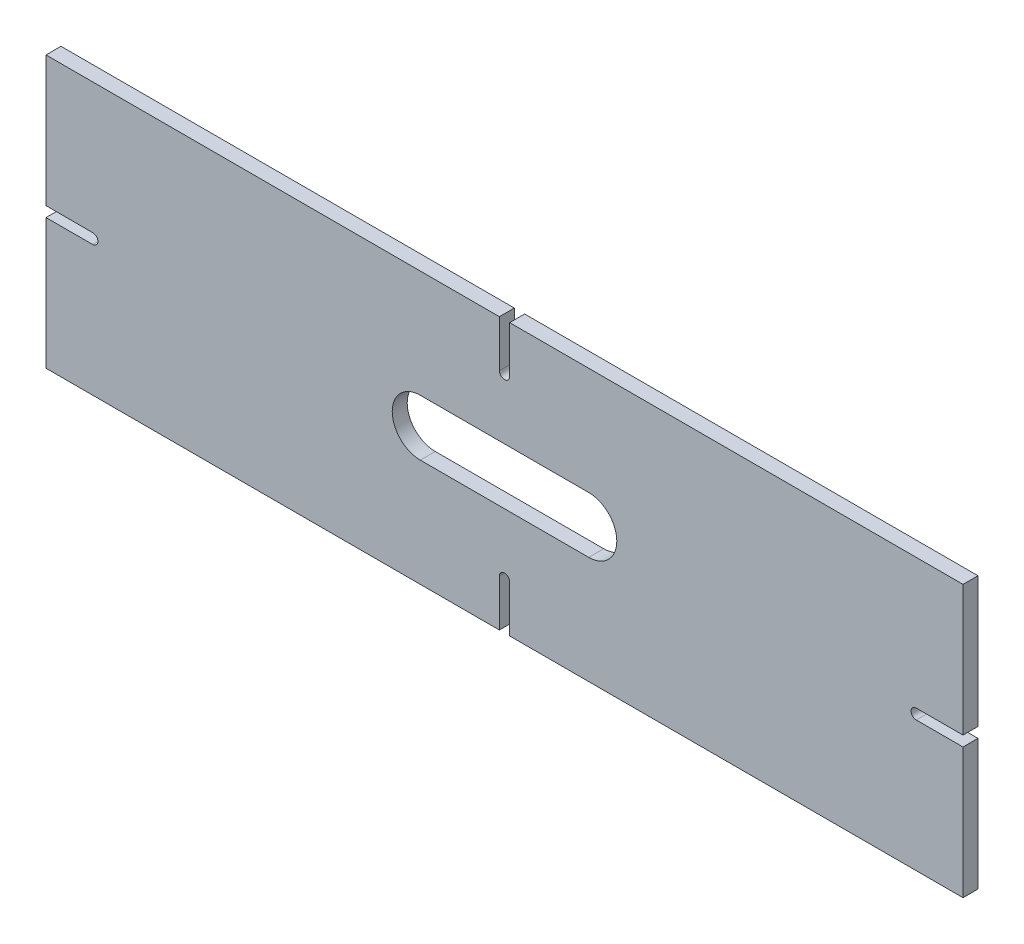
SolidWorks part; units mm, degrees
ref_plane "Front Plane" through (0, 0, 0) normal (0, 0, 1) x (1, 0, 0)
ref_plane "Top Plane" through (0, 0, 0) normal (0, 1, 0) x (1, 0, 0)
ref_plane "Right Plane" through (0, 0, 0) normal (1, 0, 0) x (0, 0, -1)
sketch "Sketch1" plane through (0, 0, 0) normal (0, 0, 1) x (1, 0, 0)
  line L0 (0, 72.5) -> (0, 47.5) construction
  line L1 (-245, -72.5) -> (245, -72.5)
  line L2 (-245, -72.5) -> (-245, 72.5)
  line L3 (-245, 72.5) -> (245, 72.5)
  line L4 (245, -72.5) -> (245, 72.5)
  line L5 (-245, -72.5) -> (245, 72.5) construction
  line L6 (-245, 72.5) -> (245, -72.5) construction
  line L7 (2.75, 72.5) -> (2.75, 47.5)
  line L8 (-2.75, 72.5) -> (-2.75, 47.5)
  line L9 (245, 0) -> (220, 0) construction
  line L10 (245, -2.75) -> (220, -2.75)
  line L11 (245, 2.75) -> (220, 2.75)
  line L12 (0, -72.5) -> (0, -47.5) construction
  line L13 (-2.75, -72.5) -> (-2.75, -47.5)
  line L14 (2.75, -72.5) -> (2.75, -47.5)
  line L15 (-245, 0) -> (-220, 0) construction
  line L16 (-245, 2.75) -> (-220, 2.75)
  line L17 (-245, -2.75) -> (-220, -2.75)
  line L18 (-45, 0) -> (45, 0) construction
  line L19 (-45, 15) -> (45, 15)
  line L20 (-45, -15) -> (45, -15)
  arc A0 (2.75, 72.5) -> (-2.75, 72.5) centre (0, 72.5) ccw
  arc A1 (-2.75, 47.5) -> (2.75, 47.5) centre (0, 47.5) ccw
  arc A2 (245, -2.75) -> (245, 2.75) centre (245, 0) ccw
  arc A3 (220, 2.75) -> (220, -2.75) centre (220, 0) ccw
  arc A4 (-2.75, -72.5) -> (2.75, -72.5) centre (0, -72.5) ccw
  arc A5 (2.75, -47.5) -> (-2.75, -47.5) centre (0, -47.5) ccw
  arc A6 (-245, 2.75) -> (-245, -2.75) centre (-245, 0) ccw
  arc A7 (-220, -2.75) -> (-220, 2.75) centre (-220, 0) ccw
  arc A8 (-45, 15) -> (-45, -15) centre (-45, 0) ccw
  arc A9 (45, -15) -> (45, 15) centre (45, 0) ccw
  point P0 (0, 0)
  point P8 (0, 60)
  point P13 (232.5, 0)
  point P20 (0, -60)
  point P27 (-232.5, 0)
  point P36 (0, 0)
  dimension "D1" = 25
  dimension "D2" = 25
  dimension "D3" = 25
  dimension "D4" = 25
  dimension "D5" = 5.5
  dimension "D6" = 5.5
  dimension "D7" = 5.5
  dimension "D8" = 5.5
  dimension "D9" = 90
  dimension "D10" = 30
  dimension "D11" = 145
  dimension "D12" = 490
extrude "Boss-Extrude3" add sketch "Sketch1" along normal blind 8 contours A7 L17 L2 L1 L13 A5 L14 L4 L10 A3 L11 L3 L7 A1 L8 L16 A9 L20 A8 L19
